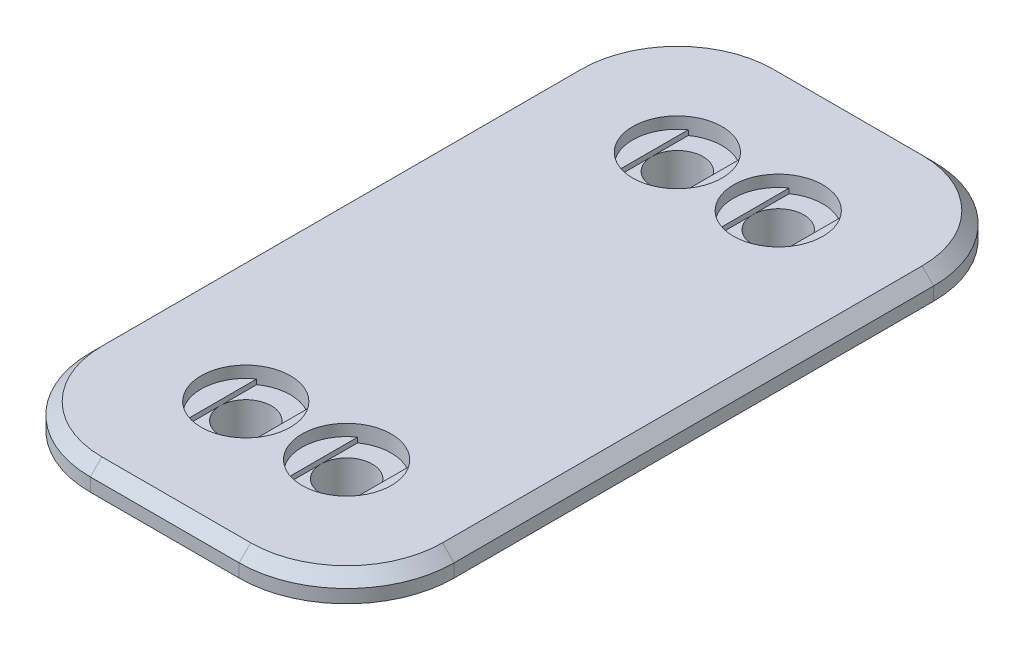
SolidWorks part; units mm, degrees
ref_plane "Front Plane" through (0, 0, 0) normal (0, 0, 1) x (1, 0, 0)
ref_plane "Top Plane" through (0, 0, 0) normal (0, 1, 0) x (1, 0, 0)
ref_plane "Right Plane" through (0, 0, 0) normal (1, 0, 0) x (0, 0, -1)
sketch "Sketch1" plane through (0, 0, 0) normal (0, 1, 0) x (1, 0, 0)
  line L0 (5.6, -14.5) -> (5.6, 14.5)
  line L1 (4.5, 15.6) -> (-4.5, 15.6)
  line L2 (-5.6, 14.5) -> (-5.6, -14.5)
  line L3 (-4.5, -15.6) -> (4.5, -15.6)
  line L4 (6, -14.5) -> (6, 14.5)
  line L5 (4.5, 16) -> (-4.5, 16)
  line L6 (-6, 14.5) -> (-6, -14.5)
  line L7 (-4.5, -16) -> (4.5, -16)
  line L8 (6, -14.5) -> (6, 14.5) construction
  line L9 (4.5, 16) -> (-4.5, 16) construction
  line L10 (-6, 14.5) -> (-6, -14.5) construction
  line L11 (-4.5, -16) -> (4.5, -16) construction
  arc A0 (4.5, -15.6) -> (5.6, -14.5) centre (4.5, -14.5) ccw
  arc A1 (5.6, 14.5) -> (4.5, 15.6) centre (4.5, 14.5) ccw
  arc A2 (-4.5, 15.6) -> (-5.6, 14.5) centre (-4.5, 14.5) ccw
  arc A3 (-5.6, -14.5) -> (-4.5, -15.6) centre (-4.5, -14.5) ccw
  arc A4 (4.5, -16) -> (6, -14.5) centre (4.5, -14.5) ccw
  arc A5 (6, 14.5) -> (4.5, 16) centre (4.5, 14.5) ccw
  arc A6 (-4.5, 16) -> (-6, 14.5) centre (-4.5, 14.5) ccw
  arc A7 (-6, -14.5) -> (-4.5, -16) centre (-4.5, -14.5) ccw
  arc A8 (4.5, -16) -> (6, -14.5) centre (4.5, -14.5) ccw construction
  arc A9 (6, 14.5) -> (4.5, 16) centre (4.5, 14.5) ccw construction
  arc A10 (-4.5, 16) -> (-6, 14.5) centre (-4.5, 14.5) ccw construction
  arc A11 (-6, -14.5) -> (-4.5, -16) centre (-4.5, -14.5) ccw construction
  dimension "D1" = 0
  dimension "D2" = 0.4
extrude "Boss-Extrude1" add sketch "Sketch1" along normal up to surface (2.3 mm away) from offset 0.2
sketch "Sketch2" plane through (0, 2.5, 0) normal (0, 1, 0) x (1, 0, 0)
  line L4 (-4.5, -21) -> (4.5, -21)
  line L5 (11, -14.5) -> (11, 14.5)
  line L6 (4.5, 21) -> (-4.5, 21)
  line L7 (-11, 14.5) -> (-11, -14.5)
  line L8 (-4.5, -21) -> (4.5, -21)
  line L9 (11, -14.5) -> (11, 14.5)
  line L10 (4.5, 21) -> (-4.5, 21)
  line L11 (-11, 14.5) -> (-11, -14.5)
  arc A4 (-11, -14.5) -> (-4.5, -21) centre (-4.5, -14.5) ccw
  arc A5 (4.5, -21) -> (11, -14.5) centre (4.5, -14.5) ccw
  arc A6 (11, 14.5) -> (4.5, 21) centre (4.5, 14.5) ccw
  arc A7 (-4.5, 21) -> (-11, 14.5) centre (-4.5, 14.5) ccw
  arc A8 (-11, -14.5) -> (-4.5, -21) centre (-4.5, -14.5) ccw
  arc A9 (4.5, -21) -> (11, -14.5) centre (4.5, -14.5) ccw
  arc A10 (11, 14.5) -> (4.5, 21) centre (4.5, 14.5) ccw
  arc A11 (-4.5, 21) -> (-11, 14.5) centre (-4.5, 14.5) ccw
  dimension "D1" = 0
extrude "Boss-Extrude2" add sketch "Sketch2" along normal up to surface (1.5 mm away)
sketch "Sketch3" plane through (0, 4, 0) normal (0, 1, 0) x (1, 0, 0)
  circle A1 centre (3.05, -13.05) radius 1.55
  circle A2 centre (3.05, -13.05) radius 1.55
  circle A11 centre (3.05, 13.05) radius 1.55
  circle A12 centre (3.05, 13.05) radius 1.55
  circle A13 centre (-3.05, 13.05) radius 1.55
  circle A14 centre (-3.05, 13.05) radius 1.55
  circle A15 centre (-3.05, -13.05) radius 1.55
  circle A16 centre (-3.05, -13.05) radius 1.55
  dimension "D1" = 0
  dimension "D6" = 0
  dimension "D7" = 0
  dimension "D8" = 0
extrude "Cut-Extrude1" cut sketch "Sketch3" against normal through all
chamfer "Chamfer1" distance 0.7 angle 45 8 edges at (-11, 4, 0) (-9.0962, 4, 19.0962) (-9.0962, 4, -19.0962) (0, 4, 21) (0, 4, -21) (9.0962, 4, 19.0962) (9.0962, 4, -19.0962) (11, 4, 0)
fillet "Fillet1" radius 0.6 8 edges at (5.2778, 0.2, 15.2778) (0, 0.2, 15.6) (-5.2778, 0.2, 15.2778) (-5.6, 0.2, 0) (-5.2778, 0.2, -15.2778) (0, 0.2, -15.6) (5.2778, 0.2, -15.2778) (5.6, 0.2, 0)
sketch "Sketch4" plane through (0, 4, 0) normal (0, 1, 0) x (1, 0, 0)
  circle A0 centre (-3.05, 13.05) radius 2.7
  circle A1 centre (3.05, 13.05) radius 2.7
  circle A2 centre (-3.05, -13.05) radius 2.7
  circle A3 centre (3.05, -13.05) radius 2.7
  dimension "D1" = 5.4
extrude "Cut-Extrude2" cut sketch "Sketch4" against normal blind 1
sketch "Sketch5" plane through (0, 3, 0) normal (0, 1, 0) x (1, 0, 0)
  line L0 (4.6, 15.2608) -> (4.6, 10.8392)
  line L1 (1.5, 15.2608) -> (1.5, 10.8392)
  line L2 (-4.6, 15.2608) -> (-4.6, 10.8392)
  line L3 (-1.5, 15.2608) -> (-1.5, 10.8392)
  line L4 (-4.6, -10.8392) -> (-4.6, -15.2608)
  line L5 (-1.5, -10.8392) -> (-1.5, -15.2608)
  line L6 (1.5, -10.8392) -> (1.5, -15.2608)
  line L7 (4.6, -10.8392) -> (4.6, -15.2608)
  circle A0 centre (-3.05, -13.05) radius 1.55 construction
  circle A1 centre (3.05, -13.05) radius 1.55 construction
  circle A2 centre (3.05, 13.05) radius 1.55 construction
  circle A3 centre (-3.05, 13.05) radius 1.55 construction
  circle A4 centre (-3.05, 13.05) radius 2.7 construction
  circle A5 centre (-3.05, -13.05) radius 2.7 construction
  circle A6 centre (3.05, -13.05) radius 2.7 construction
  circle A7 centre (3.05, 13.05) radius 2.7 construction
  circle A8 centre (-3.05, -13.05) radius 1.55 construction
  circle A9 centre (3.05, -13.05) radius 1.55 construction
  circle A10 centre (3.05, 13.05) radius 1.55 construction
  circle A11 centre (-3.05, 13.05) radius 1.55 construction
  arc A12 (-4.6, 15.2608) -> (-4.6, 10.8392) centre (-3.05, 13.05) ccw
  arc A13 (-4.6, -10.8392) -> (-4.6, -15.2608) centre (-3.05, -13.05) ccw
  arc A14 (1.5, -10.8392) -> (1.5, -15.2608) centre (3.05, -13.05) ccw
  arc A15 (1.5, 15.2608) -> (1.5, 10.8392) centre (3.05, 13.05) ccw
  arc A16 (-1.5, 10.8392) -> (-1.5, 15.2608) centre (-3.05, 13.05) ccw
  arc A17 (4.6, 10.8392) -> (4.6, 15.2608) centre (3.05, 13.05) ccw
  arc A18 (-1.5, -15.2608) -> (-1.5, -10.8392) centre (-3.05, -13.05) ccw
  arc A19 (4.6, -15.2608) -> (4.6, -10.8392) centre (3.05, -13.05) ccw
extrude "Boss-Extrude3" add sketch "Sketch5" along normal blind 0.3
